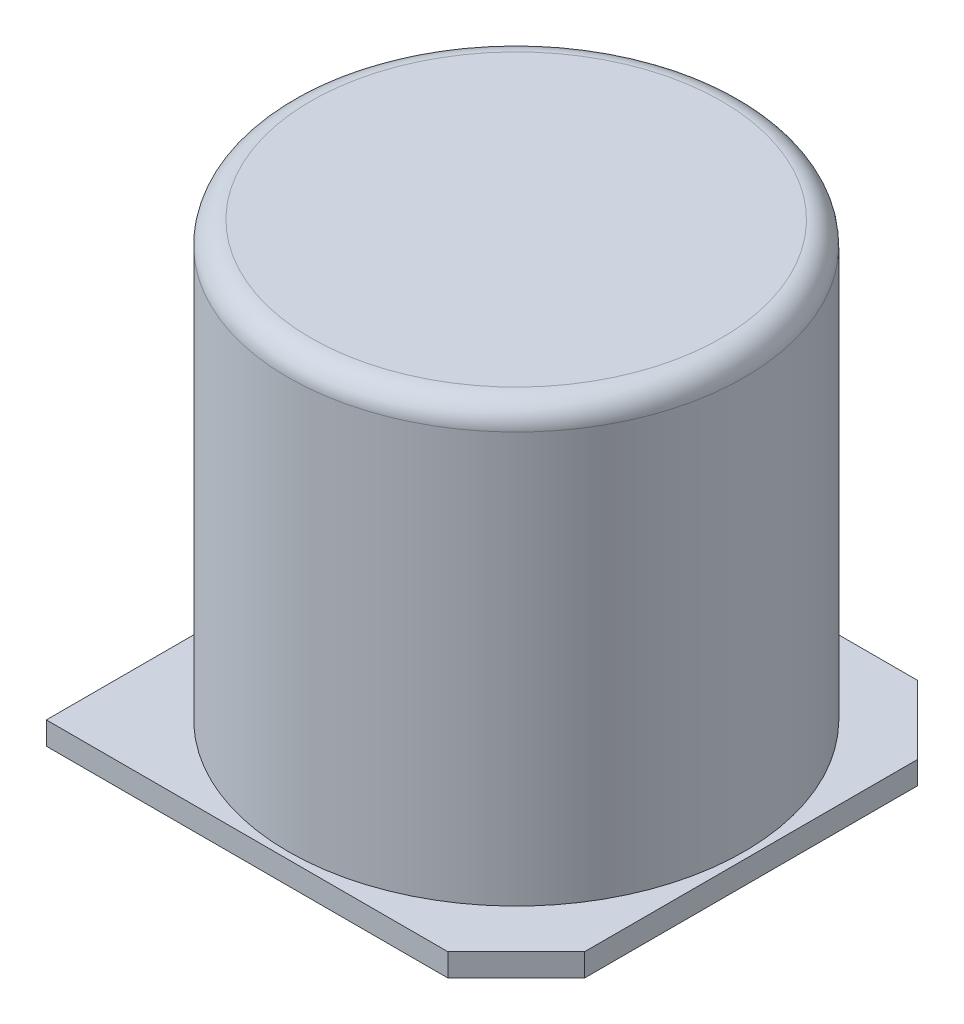
SolidWorks part; units mm, degrees
ref_plane "Front Plane" through (0, 0, 0) normal (0, 0, 1) x (1, 0, 0)
ref_plane "Top Plane" through (0, 0, 0) normal (0, 1, 0) x (1, 0, 0)
ref_plane "Right Plane" through (0, 0, 0) normal (1, 0, 0) x (0, 0, -1)
sketch "Sketch1" plane through (0, 0, 0) normal (0, 1, 0) x (1, 0, 0)
  line L1 (-5.15, -5.15) -> (5.15, -5.15)
  line L2 (-5.15, -5.15) -> (-5.15, 5.15)
  line L3 (-5.15, 5.15) -> (5.15, 5.15)
  line L4 (5.15, -5.15) -> (5.15, 5.15)
  line L5 (-5.15, -5.15) -> (5.15, 5.15) construction
  line L6 (-5.15, 5.15) -> (5.15, -5.15) construction
  point P0 (0, 0)
  dimension "D1" = 10.3
  dimension "D2" = 10.3
extrude "Boss-Extrude1" add sketch "Sketch1" along normal blind 0.5
sketch "Sketch2" plane through (0, 0.5, 0) normal (0, 1, 0) x (1, 0, 0)
  circle A0 centre (0, 0) radius 5
  dimension "D1" = 10
extrude "Boss-Extrude2" add sketch "Sketch2" along normal blind 9.5
chamfer "Chamfer1" distance 1.5 angle 45 2 edges at (5.15, 0.25, 5.15) (5.15, 0.25, -5.15)
fillet "Fillet1" radius 0.5 1 edges at (0, 10, 5)
